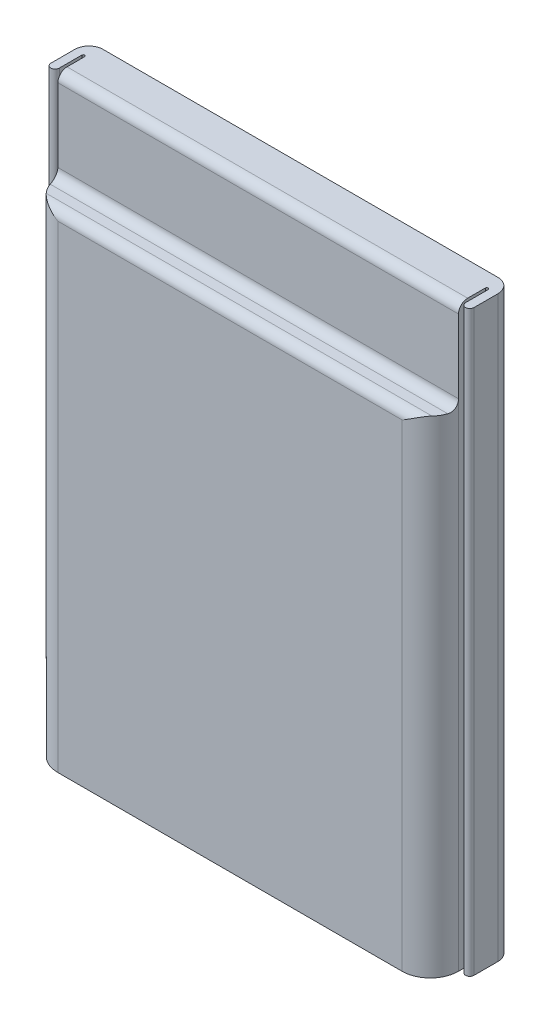
SolidWorks part; units mm, degrees
ref_plane "Front" through (0, 0, 0) normal (0, 0, 1) x (1, 0, 0)
ref_plane "Top" through (0, 0, 0) normal (0, 1, 0) x (1, 0, 0)
ref_plane "Right" through (0, 0, 0) normal (1, 0, 0) x (0, 0, -1)
sketch "Эскиз1" plane through (0, 0, 0) normal (0, 1, 0) x (1, 0, 0)
  line L0 (-14, 0) -> (14, 0)
  line L1 (-12.2, -5) -> (12.2, -5)
  line L2 (-15, -1) -> (-15, -2.7)
  line L3 (15, -1) -> (15, -2.7)
  line L4 (-14.2, -3) -> (-14.2, -1.1)
  line L5 (14.2, -1.1) -> (14.2, -3)
  line L6 (14.4, -2.7) -> (14.4, -1.1)
  line L7 (-14.4, -2.7) -> (-14.4, -1.1)
  arc A0 (-14, 0) -> (-15, -1) centre (-14, -1) ccw
  arc A1 (14, 0) -> (15, -1) centre (14, -1) cw
  arc A2 (-14.2, -3) -> (-12.2, -5) centre (-12.2, -3) ccw
  arc A3 (14.2, -3) -> (12.2, -5) centre (12.2, -3) cw
  arc A4 (15, -2.7) -> (14.4, -2.7) centre (14.7, -2.7) cw
  arc A5 (14.2, -1.1) -> (14.4, -1.1) centre (14.3, -1.1) cw
  arc A6 (-15, -2.7) -> (-14.4, -2.7) centre (-14.7, -2.7) ccw
  arc A7 (-14.2, -1.1) -> (-14.4, -1.1) centre (-14.3, -1.1) ccw
  point P20 (14.3, -1)
  point P21 (14.7, -3)
  point P27 (-14.3, -1)
  point P28 (-14.7, -3)
  dimension "D1" = 30
  dimension "D3" = 2
  dimension "D4" = 1
  dimension "D5" = 0.3
  dimension "D6" = 0.1
  dimension "D2" = 5
extrude "Бобышка-Вытянуть1" add sketch "Эскиз1" along normal mid plane 41
sketch "Эскиз2" plane through (0, 0, 0) normal (1, 0, 0) x (0, 0, -1)
  line L0 (-3, 19.85) -> (-3, 14.65)
  line L1 (-3.65, 14) -> (-4.35, 14)
  line L2 (-5, 20.5) -> (-5, 13.35)
  line L3 (-5, 20.5) -> (-5, -20.5) construction
  line L6 (-5, 20.5) -> (-2.35, 20.5)
  line L7 (0, 20.5) -> (-1, 20.5) construction
  arc A0 (-3, 14.65) -> (-3.65, 14) centre (-3.65, 14.65) cw
  arc A1 (-4.35, 14) -> (-5, 13.35) centre (-4.35, 13.35) ccw
  arc A2 (-2.35, 20.5) -> (-3, 19.85) centre (-2.35, 19.85) ccw
  dimension "D1" = 0.65
  dimension "D2" = 3
  dimension "D3" = 6.5
extrude "Вырез-Вытянуть1" cut sketch "Эскиз2" against normal up to next and the other way up to next
